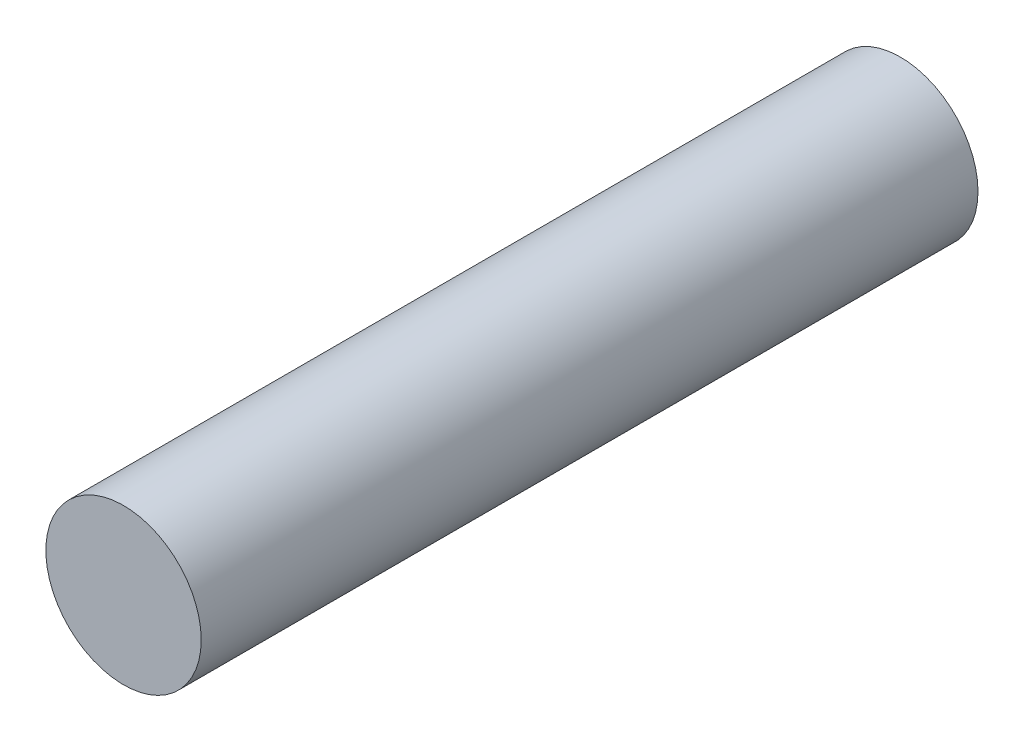
SolidWorks part; units mm, degrees
ref_plane "Front Plane" through (0, 0, 0) normal (0, 0, 1) x (1, 0, 0)
ref_plane "Top Plane" through (0, 0, 0) normal (0, 1, 0) x (1, 0, 0)
ref_plane "Right Plane" through (0, 0, 0) normal (1, 0, 0) x (0, 0, -1)
sketch "Sketch1" plane through (0, 0, 0) normal (0, 0, 1) x (1, 0, 0)
  circle A0 centre (0, 0) radius 7.5
  dimension "D1" = 15
extrude "Boss-Extrude1" add sketch "Sketch1" along normal blind 75 contours A0
